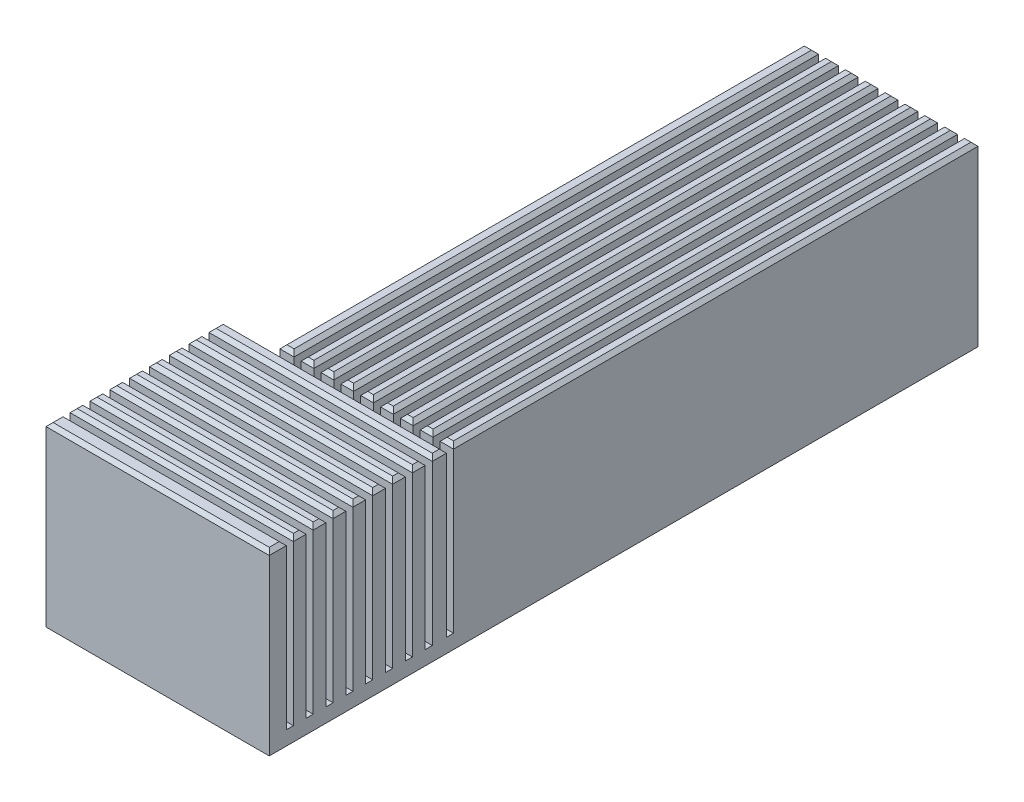
SolidWorks part; units mm, degrees
ref_plane "Front Plane" through (0, 0, 0) normal (0, 0, 1) x (1, 0, 0)
ref_plane "Top Plane" through (0, 0, 0) normal (0, 1, 0) x (1, 0, 0)
ref_plane "Right Plane" through (0, 0, 0) normal (1, 0, 0) x (0, 0, -1)
sketch "Sketch1" plane through (0, 0, 0) normal (0, 1, 0) x (1, 0, 0)
  line L0 (-18.6475, 3.791) -> (-18.6475, -21.209)
  line L1 (-18.6475, -21.209) -> (12.8525, -21.209)
  line L2 (12.8525, -21.209) -> (12.8525, 78.791)
  line L3 (12.8525, 78.791) -> (-11.6475, 78.791)
  line L4 (-11.6475, 78.791) -> (-11.6475, 3.791)
  line L5 (-11.6475, 3.791) -> (-18.6475, 3.791)
  dimension "D1" = 25
  dimension "D2" = 31.5
  dimension "D3" = 100
  dimension "D4" = 24.5
extrude "Boss-Extrude1" add sketch "Sketch1" along normal blind 25
sketch "Sketch2" plane through (0, 25, 0) normal (0, 1, 0) x (1, 0, 0)
  line L0 (12.8525, -21.209) -> (12.8525, 78.791) construction
  line L1 (-11.6475, 3.791) -> (12.8525, 3.791)
  line L2 (-11.6475, 3.791) -> (-11.6475, 4.791)
  line L3 (-11.6475, 4.791) -> (12.8525, 4.791)
  line L4 (12.8525, 3.791) -> (12.8525, 4.791)
  line L5 (-18.6475, 3.791) -> (-18.6475, -21.209) construction
  line L6 (-18.6475, 1.791) -> (12.8525, 1.791)
  line L7 (-18.6475, 1.791) -> (-18.6475, 0.791)
  line L8 (-18.6475, 0.791) -> (12.8525, 0.791)
  line L9 (12.8525, 1.791) -> (12.8525, 0.791)
  line L10 (-18.6475, -1.009) -> (-18.6475, -2.009)
  line L11 (-18.6475, -1.009) -> (12.8525, -1.009)
  line L12 (12.8525, -1.009) -> (12.8525, -2.009)
  line L13 (-18.6475, -2.009) -> (12.8525, -2.009)
  line L14 (-18.6475, -3.809) -> (-18.6475, -4.809)
  line L15 (-18.6475, -3.809) -> (12.8525, -3.809)
  line L16 (12.8525, -3.809) -> (12.8525, -4.809)
  line L17 (-18.6475, -4.809) -> (12.8525, -4.809)
  line L18 (-18.6475, -6.609) -> (-18.6475, -7.609)
  line L19 (-18.6475, -6.609) -> (12.8525, -6.609)
  line L20 (12.8525, -6.609) -> (12.8525, -7.609)
  line L21 (-18.6475, -7.609) -> (12.8525, -7.609)
  line L22 (-18.6475, -9.409) -> (-18.6475, -10.409)
  line L23 (-18.6475, -9.409) -> (12.8525, -9.409)
  line L24 (12.8525, -9.409) -> (12.8525, -10.409)
  line L25 (-18.6475, -10.409) -> (12.8525, -10.409)
  line L26 (-18.6475, -12.209) -> (-18.6475, -13.209)
  line L27 (-18.6475, -12.209) -> (12.8525, -12.209)
  line L28 (12.8525, -12.209) -> (12.8525, -13.209)
  line L29 (-18.6475, -13.209) -> (12.8525, -13.209)
  line L30 (-18.6475, -15.009) -> (-18.6475, -16.009)
  line L31 (-18.6475, -15.009) -> (12.8525, -15.009)
  line L32 (12.8525, -15.009) -> (12.8525, -16.009)
  line L33 (-18.6475, -16.009) -> (12.8525, -16.009)
  line L34 (-18.6475, -17.809) -> (-18.6475, -18.809)
  line L35 (-18.6475, -17.809) -> (12.8525, -17.809)
  line L36 (12.8525, -17.809) -> (12.8525, -18.809)
  line L37 (-18.6475, -18.809) -> (12.8525, -18.809)
  line L38 (12.8525, 78.791) -> (-11.6475, 78.791) construction
  line L39 (-9.6475, 78.791) -> (-8.6475, 78.791)
  line L40 (-9.6475, 78.791) -> (-9.6475, 4.791)
  line L41 (-9.6475, 4.791) -> (-8.6475, 4.791)
  line L42 (-8.6475, 78.791) -> (-8.6475, 4.791)
  line L43 (-11.6475, 78.791) -> (-11.6475, 3.791) construction
  line L44 (-6.8475, 78.791) -> (-6.8475, 4.791)
  line L45 (-6.8475, 78.791) -> (-5.8475, 78.791)
  line L46 (-5.8475, 78.791) -> (-5.8475, 4.791)
  line L47 (-6.8475, 4.791) -> (-5.8475, 4.791)
  line L48 (-4.0475, 78.791) -> (-4.0475, 4.791)
  line L49 (-4.0475, 78.791) -> (-3.0475, 78.791)
  line L50 (-3.0475, 78.791) -> (-3.0475, 4.791)
  line L51 (-4.0475, 4.791) -> (-3.0475, 4.791)
  line L52 (-1.2475, 78.791) -> (-1.2475, 4.791)
  line L53 (-1.2475, 78.791) -> (-0.2475, 78.791)
  line L54 (-0.2475, 78.791) -> (-0.2475, 4.791)
  line L55 (-1.2475, 4.791) -> (-0.2475, 4.791)
  line L56 (1.5525, 78.791) -> (1.5525, 4.791)
  line L57 (1.5525, 78.791) -> (2.5525, 78.791)
  line L58 (2.5525, 78.791) -> (2.5525, 4.791)
  line L59 (1.5525, 4.791) -> (2.5525, 4.791)
  line L60 (4.3525, 78.791) -> (4.3525, 4.791)
  line L61 (4.3525, 78.791) -> (5.3525, 78.791)
  line L62 (5.3525, 78.791) -> (5.3525, 4.791)
  line L63 (4.3525, 4.791) -> (5.3525, 4.791)
  line L64 (7.1525, 78.791) -> (7.1525, 4.791)
  line L65 (7.1525, 78.791) -> (8.1525, 78.791)
  line L66 (8.1525, 78.791) -> (8.1525, 4.791)
  line L67 (7.1525, 4.791) -> (8.1525, 4.791)
  line L68 (9.9525, 78.791) -> (9.9525, 4.791)
  line L69 (9.9525, 78.791) -> (10.9525, 78.791)
  line L70 (10.9525, 78.791) -> (10.9525, 4.791)
  line L71 (9.9525, 4.791) -> (10.9525, 4.791)
  line M40 (-18.6475, 3.791) -> (-18.6475, -21.209)
  line M42 (12.8525, -21.209) -> (12.8525, 78.791)
  line M43 (12.8525, 78.791) -> (-11.6475, 78.791)
  line M44 (-11.6475, 78.791) -> (-11.6475, 3.791)
  dimension "D1" = 1
  dimension "D2" = 1
  dimension "D3" = 2
  dimension "D5" = 2
  dimension "D6" = 1
  dimension "D4" = 8
  dimension "D7" = 8
extrude "Cut-Extrude1" cut sketch "Sketch2" against normal blind 23 contours L42 L40 L3 M43 | L46 L44 L3 M43 | L50 L48 L3 M43 | L54 L52 L3 M43 | L58 L56 L3 M43 | L62 L60 L3 M43 | L66 L64 L3 M43 | L70 L68 L3 M43 | L3 L1 M44 M42 | L8 L6 M40 M42 | L13 L11 M40 M42 | L17 L15 M40 M42 | L21 L19 M40 M42 | L25 L23 M40 M42 | L37 L35 M40 M42 | L33 L31 M40 M42 | L29 L28 L27 L26
chamfer "Chamfer1" distance 0.5 72 edges at (12.8525, 25, -41.791) (11.9025, 25, -4.791) (10.9525, 25, -41.791) (11.9025, 25, -78.791) (9.9525, 25, -41.791) (9.0525, 25, -4.791) (8.1525, 25, -41.791) (9.0525, 25, -78.791) (7.1525, 25, -41.791) (6.2525, 25, -4.791) (5.3525, 25, -41.791) (6.2525, 25, -78.791) (4.3525, 25, -41.791) (3.4525, 25, -4.791) (2.5525, 25, -41.791) (3.4525, 25, -78.791) (1.5525, 25, -41.791) (0.6525, 25, -4.791) (-0.2475, 25, -41.791) (0.6525, 25, -78.791) (-1.2475, 25, -41.791) (-2.1475, 25, -4.791) (-3.0475, 25, -41.791) (-2.1475, 25, -78.791) (-4.0475, 25, -41.791) (-4.9475, 25, -4.791) (-5.8475, 25, -41.791) (-4.9475, 25, -78.791) (-6.8475, 25, -41.791) (-7.7475, 25, -4.791) (-8.6475, 25, -41.791) (-7.7475, 25, -78.791) (-10.6475, 25, -78.791) (-9.6475, 25, -41.791) (-10.6475, 25, -4.791) (-11.6475, 25, -41.791) (-2.8975, 25, -1.791) (-18.6475, 25, -2.791) (-2.8975, 25, -3.791) (12.8525, 25, -2.791) (12.8525, 25, 0.109) (-2.8975, 25, 1.009) (-18.6475, 25, 0.109) (-2.8975, 25, -0.791) (12.8525, 25, 2.909) (-2.8975, 25, 3.809) (-18.6475, 25, 2.909) (-2.8975, 25, 2.009) (12.8525, 25, 5.709) (-2.8975, 25, 6.609) (-18.6475, 25, 5.709) (-2.8975, 25, 4.809) (12.8525, 25, 8.509) (-2.8975, 25, 9.409) (-18.6475, 25, 8.509) (-2.8975, 25, 7.609) (-2.8975, 25, 10.409) (12.8525, 25, 11.309) (-2.8975, 25, 12.209) (-18.6475, 25, 11.309) (12.8525, 25, 14.109) (-2.8975, 25, 15.009) (-18.6475, 25, 14.109) (-2.8975, 25, 13.209) (12.8525, 25, 16.909) (-2.8975, 25, 17.809) (-18.6475, 25, 16.909) (-2.8975, 25, 16.009) (12.8525, 25, 20.009) (-2.8975, 25, 21.209) (-18.6475, 25, 20.009) (-2.8975, 25, 18.809)
